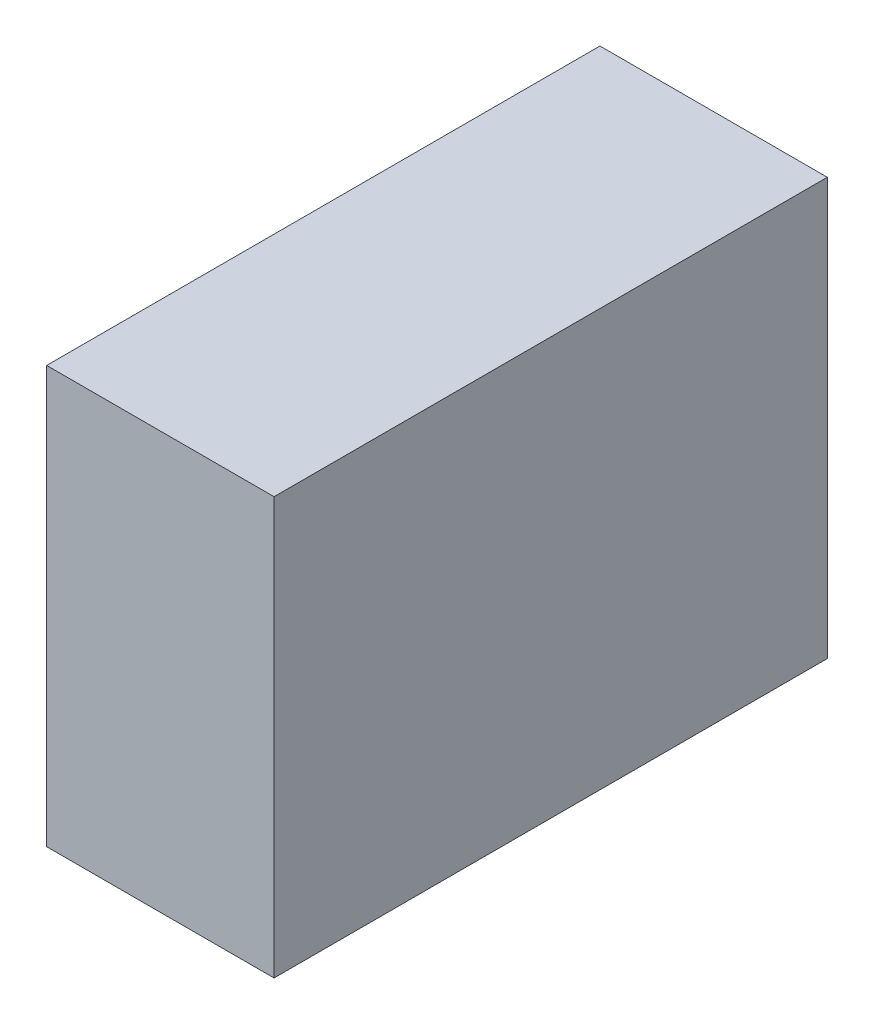
SolidWorks part; units mm, degrees
ref_plane "Front" through (0, 0, 0) normal (0, 0, 1) x (1, 0, 0)
ref_plane "Top" through (0, 0, 0) normal (0, 1, 0) x (1, 0, 0)
ref_plane "Right" through (0, 0, 0) normal (1, 0, 0) x (0, 0, -1)
sketch "Sketch1" plane through (0, 0, 0) normal (0, 1, 0) x (1, 0, 0)
  line L1 (-381, 927.1) -> (381, 927.1)
  line L2 (-381, 927.1) -> (-381, -927.1)
  line L3 (-381, -927.1) -> (381, -927.1)
  line L4 (381, 927.1) -> (381, -927.1)
  line L5 (-381, 927.1) -> (381, -927.1) construction
  line L6 (-381, -927.1) -> (381, 927.1) construction
  point P0 (0, 0)
  dimension "D1" = 762
  dimension "D2" = 1854.2
extrude "Boss-Extrude1" add sketch "Sketch1" along normal blind 1397
